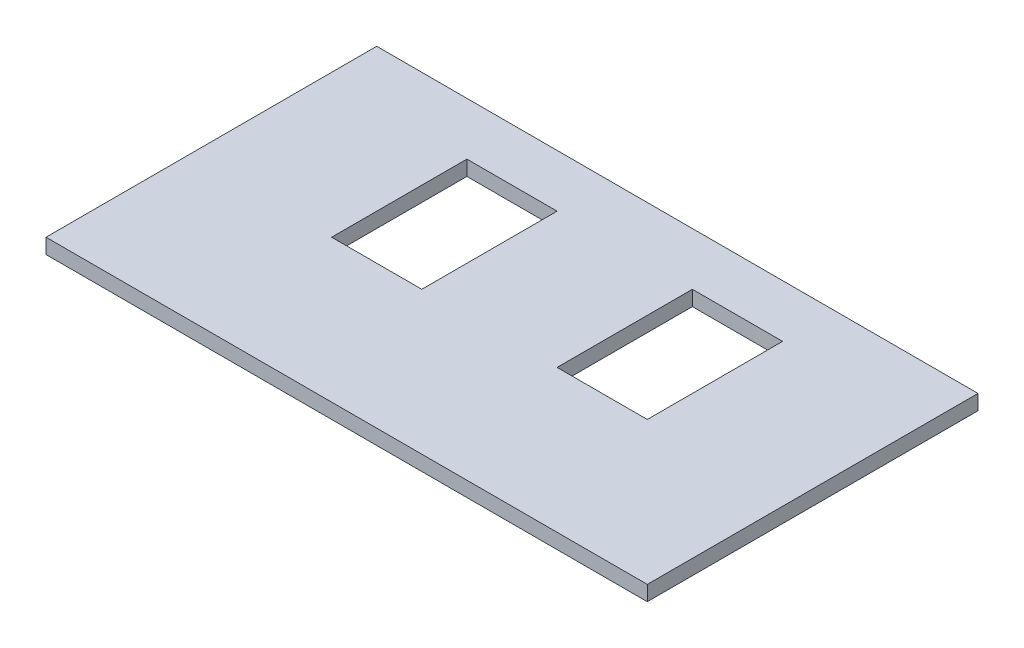
SolidWorks part; units mm, degrees
ref_plane "前视基准面" through (0, 0, 0) normal (0, 0, 1) x (1, 0, 0)
ref_plane "上视基准面" through (0, 0, 0) normal (0, 1, 0) x (1, 0, 0)
ref_plane "右视基准面" through (0, 0, 0) normal (1, 0, 0) x (0, 0, -1)
other "Configuration Table"
sketch "草图1" plane through (0, 0, 0) normal (0, 1, 0) x (1, 0, 0)
  line L0 (100, 110) -> (100, 0) construction
  line L1 (0, 0) -> (200, 0)
  line L2 (0, 0) -> (0, 110)
  line L3 (0, 110) -> (200, 110)
  line L4 (200, 0) -> (200, 110)
  line L5 (47.5, 92.5) -> (77.5, 92.5)
  line L6 (47.5, 92.5) -> (47.5, 47.5)
  line L7 (47.5, 47.5) -> (77.5, 47.5)
  line L8 (77.5, 92.5) -> (77.5, 47.5)
  line L13 (152.5, 92.5) -> (152.5, 47.5)
  line L14 (152.5, 92.5) -> (122.5, 92.5)
  line L15 (122.5, 92.5) -> (122.5, 47.5)
  line L16 (152.5, 47.5) -> (122.5, 47.5)
  point P15 (0, 0)
  dimension "D1" = 200
  dimension "D2" = 110
  dimension "D3" = 45
  dimension "D4" = 30
  dimension "D5" = 17.5
  dimension "D6" = 22.5
extrude "凸台-拉伸1" add sketch "草图1" along normal blind 5
